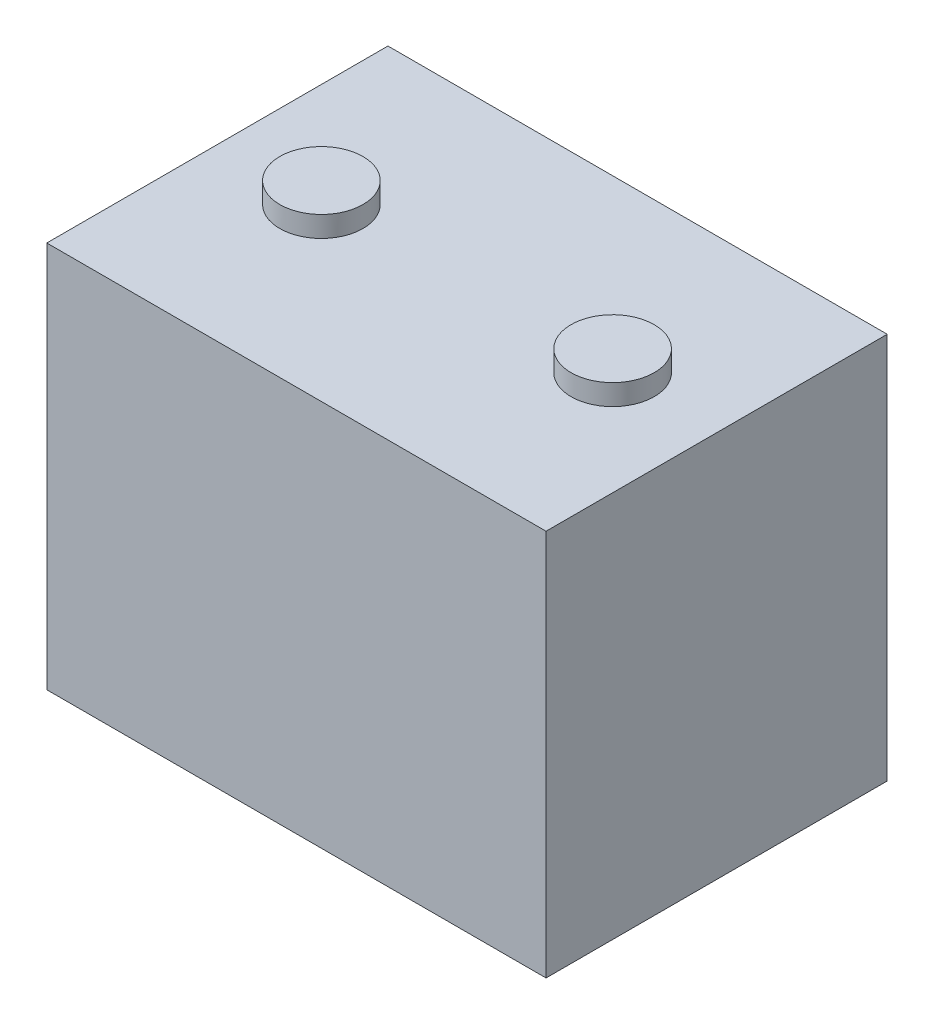
SolidWorks part; units mm, degrees
ref_plane "Plan de face" through (0, 0, 0) normal (0, 0, 1) x (1, 0, 0)
ref_plane "Plan de dessus" through (0, 0, 0) normal (0, 1, 0) x (1, 0, 0)
ref_plane "Plan de droite" through (0, 0, 0) normal (1, 0, 0) x (0, 0, -1)
sketch "Esquisse1" plane through (0, 0, 0) normal (0, 0, 1) x (1, 0, 0)
  line L1 (-87.5833, 66.75) -> (32.4167, 66.75)
  line L2 (-87.5833, 66.75) -> (-87.5833, -26.25)
  line L3 (-87.5833, -26.25) -> (32.4167, -26.25)
  line L4 (32.4167, 66.75) -> (32.4167, -26.25)
  line L5 (-87.5833, 66.75) -> (32.4167, -26.25) construction
  line L6 (-87.5833, -26.25) -> (32.4167, 66.75) construction
  point P0 (-27.5833, 20.25)
  dimension "D1" = 120
  dimension "D2" = 93
extrude "Boss.-Extru.1" add sketch "Esquisse1" along normal blind 82
sketch "Esquisse2" plane through (0, 66.75, 0) normal (0, 1, 0) x (1, 0, 0)
  line L0 (-27.5833, 0) -> (-27.5833, -82) construction
  line L1 (32.4167, 0) -> (-87.5833, 0) construction
  line L2 (32.4167, -82) -> (-87.5833, -82) construction
  line L3 (-87.5833, -82) -> (-87.5833, 0) construction
  circle A0 centre (-62.5833, -41) radius 10
  circle A1 centre (7.4167, -41) radius 10
  dimension "D1" = 20
  dimension "D2" = 41
  dimension "D3" = 25
extrude "Boss.-Extru.2" add sketch "Esquisse2" along normal blind 5
